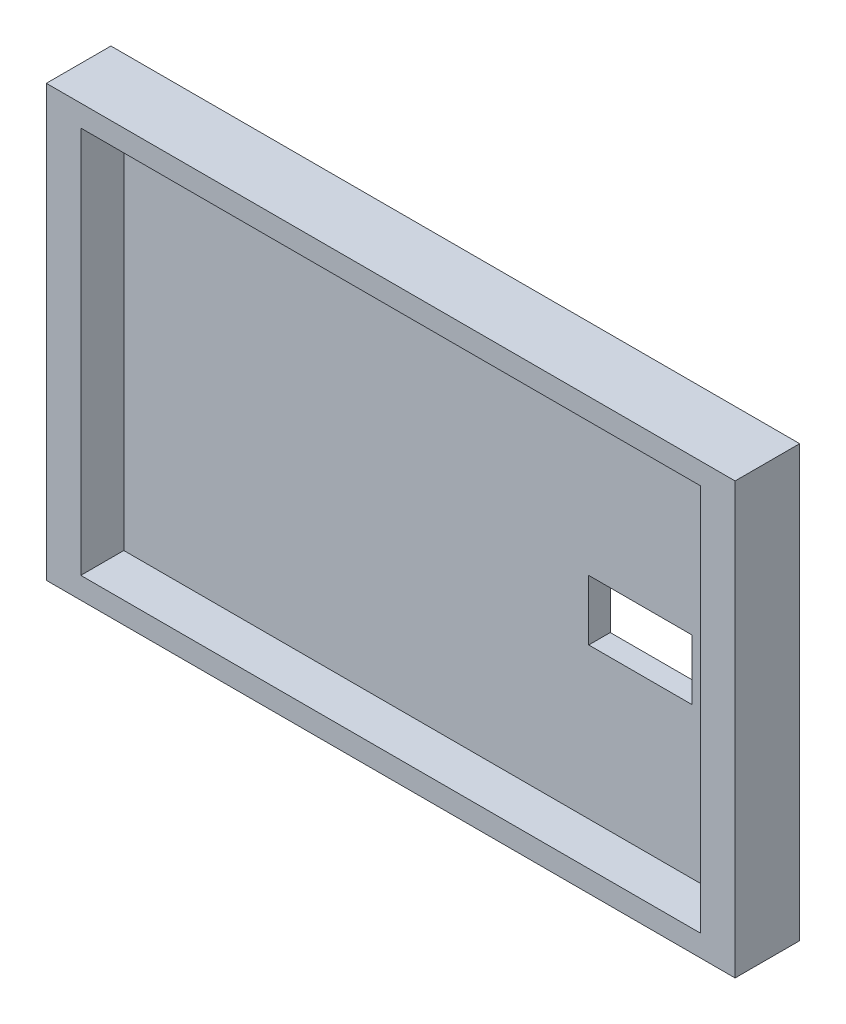
SolidWorks part; units mm, degrees
ref_plane "Plan de face" through (0, 0, 0) normal (0, 0, 1) x (1, 0, 0)
ref_plane "Plan de dessus" through (0, 0, 0) normal (0, 1, 0) x (1, 0, 0)
ref_plane "Plan de droite" through (0, 0, 0) normal (1, 0, 0) x (0, 0, -1)
sketch "Esquisse1" plane through (0, 0, 0) normal (0, 0, 1) x (1, 0, 0)
  line L1 (72, 45) -> (-72, 45)
  line L2 (72, 45) -> (72, -45)
  line L3 (72, -45) -> (-72, -45)
  line L4 (-72, 45) -> (-72, -45)
  line L5 (72, 45) -> (-72, -45) construction
  line L6 (72, -45) -> (-72, 45) construction
  line L7 (-80, 50) -> (80, 50)
  line L8 (-80, 50) -> (-80, -50)
  line L9 (-80, -50) -> (80, -50)
  line L10 (80, 50) -> (80, -50)
  line L11 (-80, 50) -> (80, -50) construction
  line L12 (-80, -50) -> (80, 50) construction
  point P0 (0, 0)
  point P6 (0, 0)
  dimension "D1" = 160
  dimension "D2" = 144
  dimension "D3" = 90
  dimension "D4" = 100
extrude "profondeur couvercle" add sketch "Esquisse1" along normal blind 15
sketch "Esquisse2" plane through (0, 0, 0) normal (0, 0, 1) x (1, 0, 0)
  line L1 (72, 45) -> (-72, 45)
  line L2 (72, 45) -> (72, -45)
  line L3 (72, -45) -> (-72, -45)
  line L4 (-72, 45) -> (-72, -45)
  line L5 (72, 45) -> (-72, -45) construction
  line L6 (72, -45) -> (-72, 45) construction
  point P0 (0, 0)
extrude "profondeur fond" add sketch "Esquisse2" along normal blind 5
sketch "Esquisse3" plane through (0, 0, 0) normal (0, 0, 1) x (1, 0, 0)
  line L0 (80, -50) -> (80, 50) construction
  line L1 (36, 4) -> (60, 4)
  line L2 (36, 4) -> (36, -10)
  line L3 (36, -10) -> (60, -10)
  line L4 (60, 4) -> (60, -10)
  line L5 (36, 4) -> (60, -10) construction
  line L6 (36, -10) -> (60, 4) construction
  line L7 (-80, -50) -> (80, -50) construction
  point P0 (48, -3)
  dimension "D1" = 24
  dimension "D2" = 14
  dimension "D3" = 20
  dimension "D4" = 40
extrude "ecran heltec" cut sketch "Esquisse3" along normal blind 21
